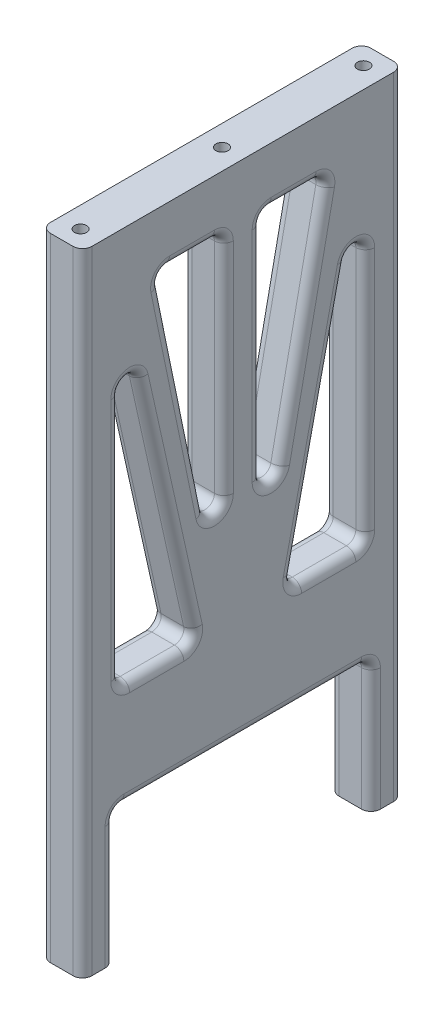
SolidWorks part; units mm, degrees
ref_plane "Front Plane" through (0, 0, 0) normal (0, 0, 1) x (1, 0, 0)
ref_plane "Top Plane" through (0, 0, 0) normal (0, 1, 0) x (1, 0, 0)
ref_plane "Right Plane" through (0, 0, 0) normal (1, 0, 0) x (0, 0, -1)
sketch "Sketch1" plane through (0, 0, 0) normal (1, 0, 0) x (0, 0, -1)
  line L1 (-37.5, -17.5) -> (37.5, -17.5) construction
  line L2 (-37.5, -17.5) -> (-37.5, 17.5) construction
  line L3 (-37.5, 17.5) -> (37.5, 17.5) construction
  line L4 (37.5, -17.5) -> (37.5, 17.5) construction
  line L5 (-37.5, -17.5) -> (37.5, 17.5) construction
  line L6 (-37.5, 17.5) -> (37.5, -17.5) construction
  line L7 (-42.5, -17.5) -> (42.5, -17.5)
  line L8 (-42.5, -17.5) -> (-42.5, 25)
  line L9 (-42.5, 25) -> (42.5, 25)
  line L10 (42.5, -17.5) -> (42.5, 25)
  line L11 (-34, -17.5) -> (34, -17.5)
  line L12 (-34, -17.5) -> (-34, 17.5)
  line L13 (-34, 17.5) -> (34, 17.5)
  line L14 (34, -17.5) -> (34, 17.5)
  line L15 (-42.5, 25) -> (42.5, 25)
  line L16 (-42.5, 25) -> (-42.5, 150)
  line L17 (-42.5, 150) -> (42.5, 150)
  line L18 (42.5, 25) -> (42.5, 150)
  line L19 (-32.5, 135) -> (32.5, 135)
  line L20 (-32.5, 135) -> (-32.5, 45)
  line L21 (-32.5, 45) -> (32.5, 45)
  line L22 (32.5, 135) -> (32.5, 45)
  point P0 (0, 0)
  dimension "D12" = 10
  dimension "D1" = 75
  dimension "D2" = 35
  dimension "D3" = 42.5
  dimension "D4" = 5
  dimension "D5" = 5
  dimension "D6" = 3.5
  dimension "D7" = 3.5
  dimension "D8" = 167.5
  dimension "D9" = 27.5
  dimension "D10" = 15
  dimension "D11" = 10
extrude "Boss-Extrude1" add sketch "Sketch1" along normal blind 11
sketch "Sketch2" plane through (11, 0, 0) normal (1, 0, 0) x (0, 0, -1)
  line L0 (-32.5, 135) -> (-12.5, 45)
  line L1 (-32.5, 135) -> (32.5, 135)
  line L2 (-32.5, 135) -> (-32.5, 45)
  line L3 (-32.5, 45) -> (32.5, 45)
  line L4 (32.5, 135) -> (32.5, 45)
  line L5 (32.5, 135) -> (12.5, 45)
  line L6 (-22.5, 135) -> (-5, 50)
  line L7 (-5, 50) -> (5, 50)
  line L8 (5, 50) -> (22.5, 135)
  line L9 (0, 135) -> (0, 45)
  line L10 (-5, 50) -> (-5, 135)
  line L11 (5, 50) -> (5, 135)
  line M22 (32.5, 45) -> (-32.5, 45)
  line M24 (-32.5, 135) -> (32.5, 135)
  dimension "D1" = 20
  dimension "D2" = 20
  dimension "D3" = 5
  dimension "D5" = 10
  dimension "D6" = 10
  dimension "D7" = 5
  dimension "D8" = 5
extrude "Boss-Extrude2" add sketch "Sketch2" against normal through all contours L9 L7 L6 L0 M24 M22 | L10 L7 L9 M24 | L7 L11 L9 M24 | L7 L9 L3 L5 L8 M24
sketch "Sketch3" plane through (0, -17.5, 0) normal (0, -1, 0) x (1, 0, 0)
  line L0 (0, 0) -> (11, 0) construction
  line L1 (11, 34) -> (11, -34) construction
  line L2 (5.5, 0) -> (5.5, 37.5) construction
  circle A0 centre (5.5, 37.5) radius 1.5
  circle A1 centre (5.5, -37.5) radius 1.5
  dimension "D2" = 3
  dimension "D1" = 37.5
extrude "Cut-Extrude1" cut sketch "Sketch3" against normal blind 10
sketch "Sketch4" plane through (0, 150, 0) normal (0, 1, 0) x (1, 0, 0)
  line L0 (0, 0) -> (11, 0) construction
  line L1 (0, -42.5) -> (0, 42.5) construction
  line L2 (11, -42.5) -> (11, 42.5) construction
  line L3 (5.5, 0) -> (5.5, 37.5) construction
  circle A0 centre (5.5, 37.5) radius 1.6
  circle A1 centre (5.5, -37.5) radius 1.6
  circle A2 centre (5.5, 0) radius 1.6
  dimension "D2" = 3.2
  dimension "D3" = 3.2
  dimension "D1" = 37.5
extrude "Cut-Extrude2" cut sketch "Sketch4" against normal blind 10
fillet "Fillet1" radius 2.5 48 edges at (0, 90, 32.5) (11, 90, 32.5) (11, 90, 22.5) (0, 90, 22.5) (11, 92.5, 13.75) (0, 92.5, 13.75) (11, 92.5, 5) (0, 92.5, 5) (11, 92.5, -5) (0, 92.5, -5) (11, 92.5, -13.75) (0, 92.5, -13.75) (0, 90, -32.5) (11, 90, -32.5) (11, 90, -22.5) (0, 90, -22.5) (0, 45, 22.5) (11, 45, 22.5) (5.5, 45, 32.5) (5.5, 45, 12.5) (0, 135, 13.75) (11, 135, 13.75) (5.5, 135, 5) (5.5, 135, 22.5) (11, 135, -13.75) (0, 135, -13.75) (5.5, 135, -5) (5.5, 135, -22.5) (5.5, 45, -32.5) (0, 45, -22.5) (11, 45, -22.5) (5.5, 45, -12.5) (5.5, 135, 32.5) (5.5, 50, 5) (5.5, 50, -5) (5.5, 135, -32.5) (0, 66.25, 42.5) (11, 66.25, 42.5) (0, 66.25, -42.5) (11, 66.25, -42.5) (0, 17.5, 0) (11, 17.5, 0) (5.5, 17.5, -34) (5.5, 17.5, 34) (0, 0, 34) (11, 0, 34) (0, 0, -34) (11, 0, -34)
